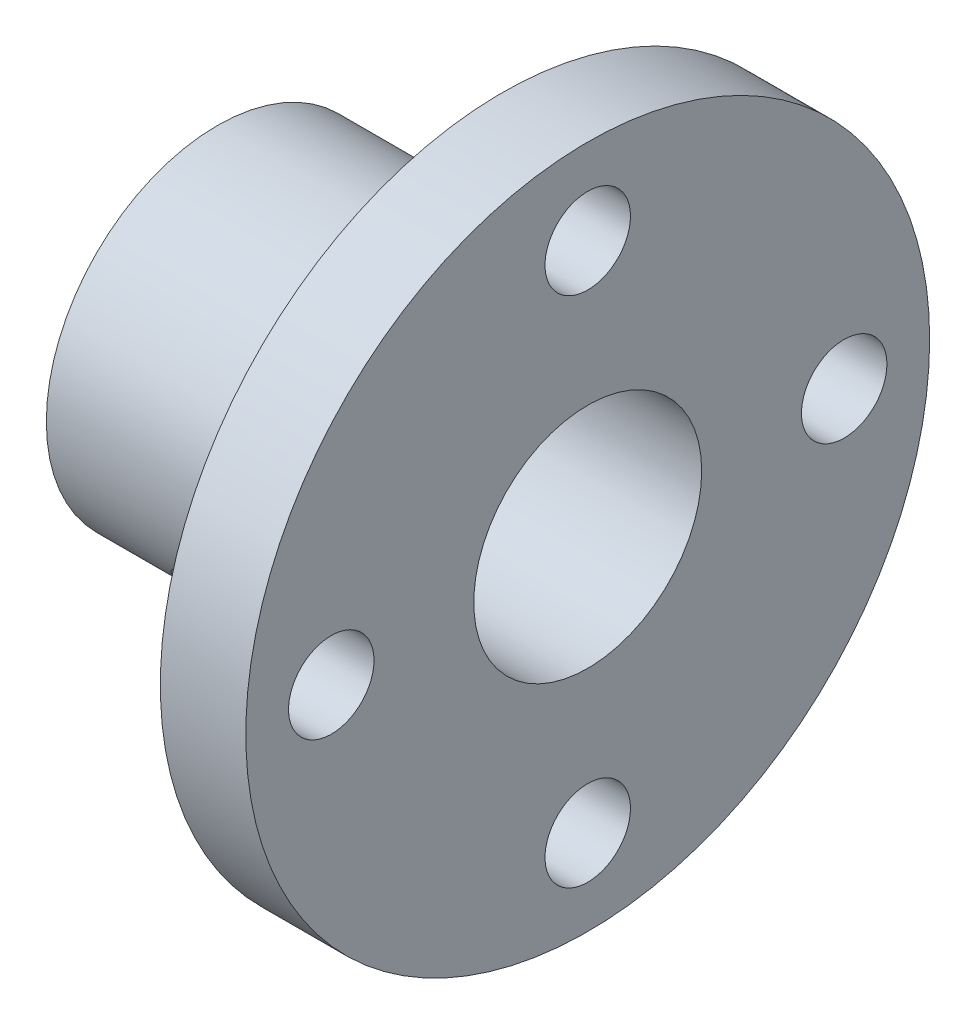
SolidWorks part; units mm, degrees
ref_plane "Front Plane" through (0, 0, 0) normal (0, 0, 1) x (1, 0, 0)
ref_plane "Top Plane" through (0, 0, 0) normal (0, 1, 0) x (1, 0, 0)
ref_plane "Right Plane" through (0, 0, 0) normal (1, 0, 0) x (0, 0, -1)
sketch "Sketch1" plane through (0, 0, 0) normal (1, 0, 0) x (0, 0, -1)
  circle A0 centre (0, 0) radius 4
  circle A1 centre (0, 0) radius 6
  dimension "D1" = 12
  dimension "D2" = 8
extrude "Boss-Extrude1" add sketch "Sketch1" along normal blind 10
sketch "Sketch2" plane through (10, 0, 0) normal (1, 0, 0) x (0, 0, -1)
  line L0 (-12, 0) -> (-6, 0) construction
  circle A0 centre (0, 0) radius 4
  circle A1 centre (0, 0) radius 12
  circle A2 centre (0, 0) radius 6 construction
  circle A3 centre (0, 0) radius 9
  circle A4 centre (-9, 0) radius 1.5
  circle A5 centre (0, 9) radius 1.5
  circle A6 centre (9, 0) radius 1.5
  circle A7 centre (0, -9) radius 1.5
  point P10 (-9, 0)
  point P22 (0, 0)
  dimension "D1" = 24
  dimension "D2" = 4
  dimension "D3" = 18
extrude "Boss-Extrude3" add sketch "Sketch2" along normal blind 3
ref_plane "Plane1" through (0, -4.2426, 4.2426) normal (0, -0.7071, 0.7071) x (-1, 0, 0)
sketch "Sketch3" plane through (0, -4.2426, 4.2426) normal (0, -0.7071, 0.7071) x (-1, 0, 0)
  line L0 (0, 6) -> (0, -6) construction
  line L1 (0, 0) -> (-10, 0) construction
  line L2 (-10, -12) -> (-10, 12) construction
  circle A0 centre (-5, 0) radius 2
extrude "Cut-Extrude1" cut sketch "Sketch3" against normal blind 3
